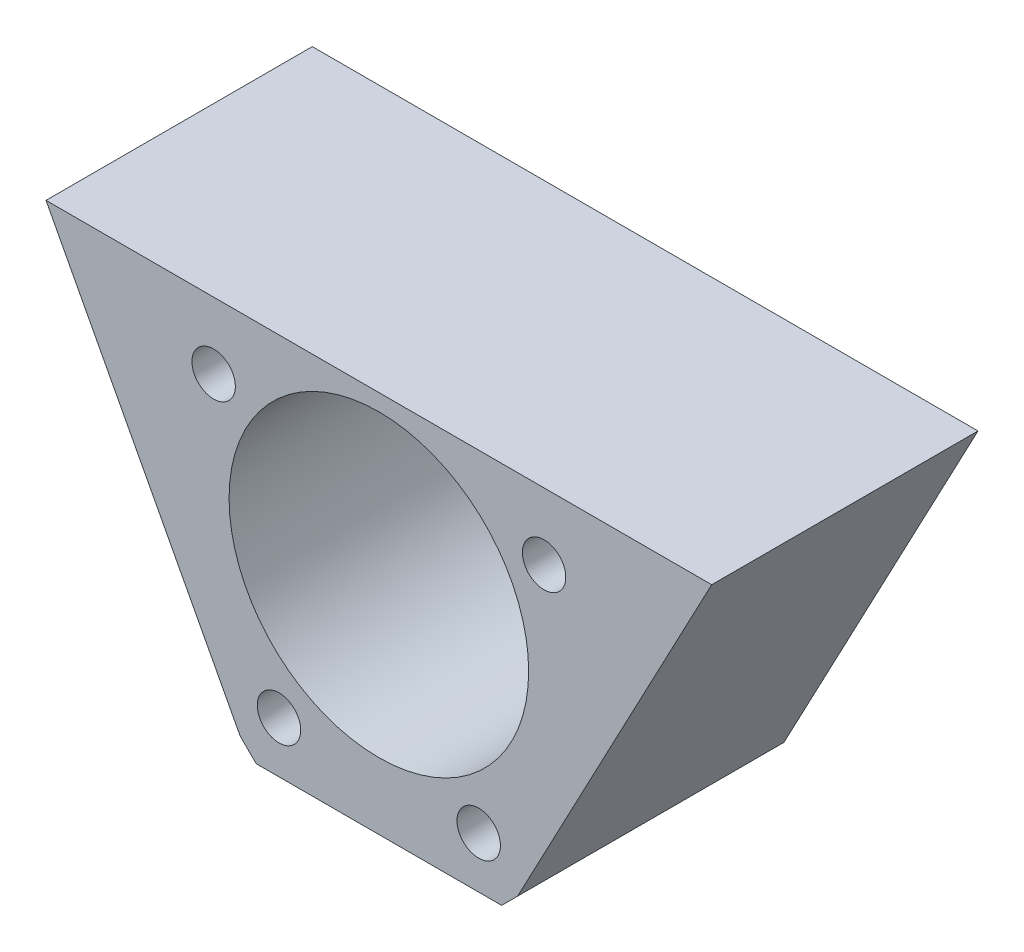
SolidWorks part; units mm, degrees
ref_plane "Front Plane" through (0, 0, 0) normal (0, 0, 1) x (1, 0, 0)
ref_plane "Top Plane" through (0, 0, 0) normal (0, 1, 0) x (1, 0, 0)
ref_plane "Right Plane" through (0, 0, 0) normal (1, 0, 0) x (0, 0, -1)
sketch "Sketch1" plane through (0, 0, 0) normal (0, 0, 1) x (1, 0, 0)
  line L0 (-88.9, 15.875) -> (533.4, 15.875) construction
  line L1 (-31.75, 15.875) -> (31.75, 15.875)
  line L10 (-31.75, 15.875) -> (-13.2358, -19.1109)
  line L11 (-13.2358, -19.1109) -> (-11.7091, -20.6375)
  line L12 (-11.7091, -20.6375) -> (11.7091, -20.6375)
  line L13 (11.7091, -20.6375) -> (13.2358, -19.1109)
  line L14 (13.2358, -19.1109) -> (31.75, 15.875)
  line L15 (31.75, 15.875) -> (31.75, 39.116)
  line L16 (31.75, 39.116) -> (29.591, 41.275)
  line L17 (29.591, 41.275) -> (-29.591, 41.275)
  line L18 (-29.591, 41.275) -> (-31.75, 39.116)
  line L19 (-31.75, 39.116) -> (-31.75, 15.875)
  line L20 (-31.75, 15.875) -> (-13.2358, -19.1109)
  line L21 (-13.2358, -19.1109) -> (-11.7091, -20.6375)
  line L22 (-11.7091, -20.6375) -> (11.7091, -20.6375)
  line L23 (11.7091, -20.6375) -> (13.2358, -19.1109)
  line L24 (13.2358, -19.1109) -> (31.75, 15.875)
  dimension "D1" = 0
extrude "Boss-Extrude1" add sketch "Sketch1" along normal blind 25.4
sketch "Sketch2" plane through (0, 0, 0) normal (0, 0, -1) x (-1, 0, 0)
  arc A0 (-7.4549, -15.7603) -> (-11.5951, -15.7603) centre (-9.525, -15.7603) ccw construction
  arc A1 (11.5951, -15.7603) -> (7.4549, -15.7603) centre (9.525, -15.7603) ccw construction
  arc A2 (17.8304, 9.525) -> (13.6902, 9.525) centre (15.7603, 9.525) ccw construction
  arc A3 (-13.6902, 9.525) -> (-17.8304, 9.525) centre (-15.7603, 9.525) ccw construction
  arc A4 (13.6902, 9.525) -> (17.8304, 9.525) centre (15.7603, 9.525) ccw construction
  arc A5 (7.4549, -15.7603) -> (11.5951, -15.7603) centre (9.525, -15.7603) ccw construction
  arc A6 (-17.8304, 9.525) -> (-13.6902, 9.525) centre (-15.7603, 9.525) ccw construction
  arc A7 (-11.5951, -15.7603) -> (-7.4549, -15.7603) centre (-9.525, -15.7603) ccw construction
  arc A8 (-7.4549, -15.7603) -> (-11.5951, -15.7603) centre (-9.525, -15.7603) ccw
  arc A9 (11.5951, -15.7603) -> (7.4549, -15.7603) centre (9.525, -15.7603) ccw
  arc A10 (17.8304, 9.525) -> (13.6902, 9.525) centre (15.7603, 9.525) ccw
  arc A11 (-13.6902, 9.525) -> (-17.8304, 9.525) centre (-15.7603, 9.525) ccw
  arc A12 (13.6902, 9.525) -> (17.8304, 9.525) centre (15.7603, 9.525) ccw
  arc A13 (7.4549, -15.7603) -> (11.5951, -15.7603) centre (9.525, -15.7603) ccw
  arc A14 (-17.8304, 9.525) -> (-13.6902, 9.525) centre (-15.7603, 9.525) ccw
  arc A15 (-11.5951, -15.7603) -> (-7.4549, -15.7603) centre (-9.525, -15.7603) ccw
  arc A16 (-14.2875, 0) -> (14.2875, 0) centre (0, 0) ccw construction
  arc A17 (14.2875, 0) -> (-14.2875, 0) centre (0, 0) ccw construction
  arc A18 (-14.2875, 0) -> (14.2875, 0) centre (0, 0) ccw
  arc A19 (14.2875, 0) -> (-14.2875, 0) centre (0, 0) ccw
extrude "Cut-Extrude1" cut sketch "Sketch2" against normal through all
